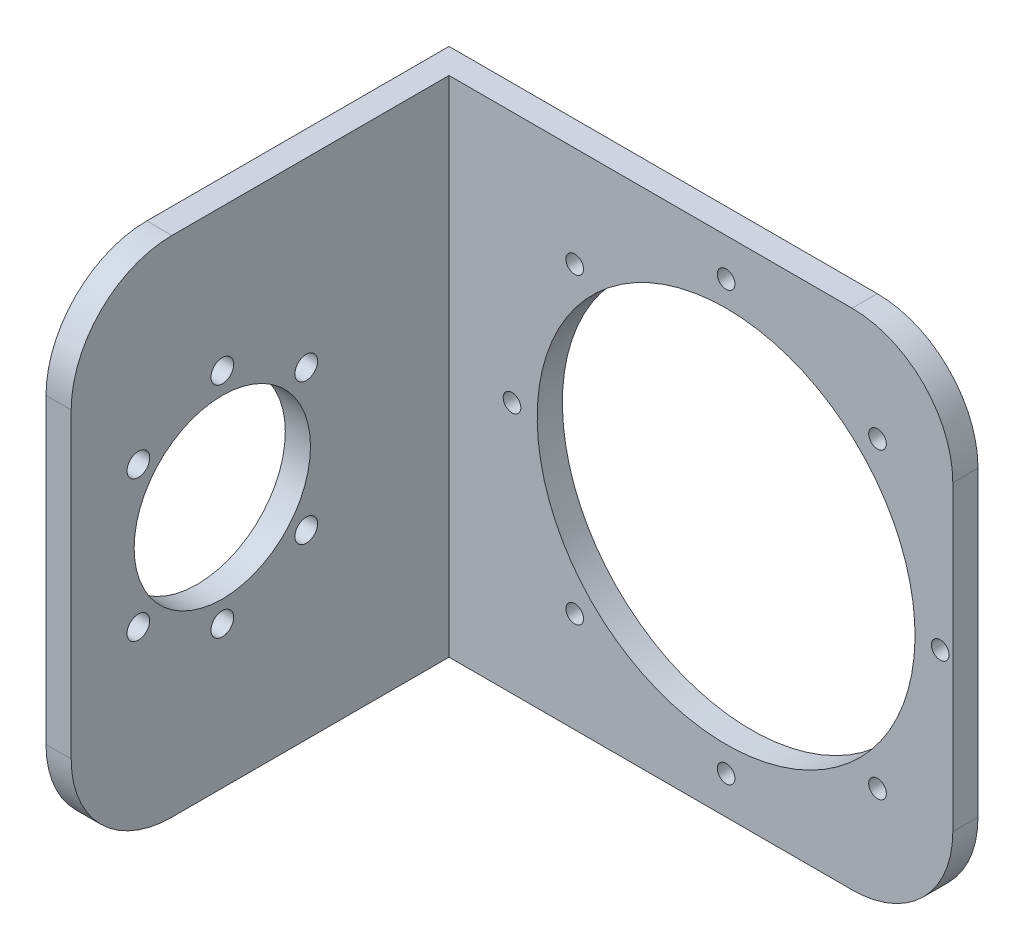
SolidWorks part; units mm, degrees
material "6061 合金"
ref_plane "前视基准面" through (0, 0, 0) normal (0, 0, 1) x (1, 0, 0)
ref_plane "上视基准面" through (0, 0, 0) normal (0, 1, 0) x (1, 0, 0)
ref_plane "右视基准面" through (0, 0, 0) normal (1, 0, 0) x (0, 0, -1)
other "Configuration Table"
sketch "草图1" plane through (0, 0, 0) normal (1, 0, 0) x (0, 0, -1)
  line L0 (-83.5786, 0) -> (71.0535, 0) construction
  line L1 (0, 49.275) -> (0, -51.1598) construction
  line L3 (-40, 50) -> (40, 50)
  line L4 (-40, 50) -> (-40, -50)
  line L5 (-40, -50) -> (40, -50)
  line L6 (40, 50) -> (40, -50)
  dimension "D1" = 80
  dimension "D2" = 100
extrude "凸台-拉伸1" add sketch "草图1" along normal blind 5
sketch "草图3" plane through (5, 0, 0) normal (1, 0, 0) x (0, 0, -1)
  line L0 (40, 50) -> (-40, 50) construction
  line L1 (35, 50) -> (40, 50)
  line L2 (35, 50) -> (35, -50)
  line L3 (35, -50) -> (40, -50)
  line L4 (40, 50) -> (40, -50)
  line L5 (0, 33.3664) -> (0, -30.3664) construction
  line L6 (-35, -50) -> (-40, -50)
  line L7 (-40, 50) -> (-40, -50)
  line L8 (-35, 50) -> (-40, 50)
  line L9 (-35, 50) -> (-35, -50)
  dimension "D1" = 5
extrude "凸台-拉伸2" add sketch "草图3" along normal blind 100 contours L2 L1 L4 L3
sketch "草图4" plane through (0, 0, 0) normal (-1, 0, 0) x (0, 0, 1)
  line L0 (-42.5996, 0) -> (43.5329, 0) construction
  line L1 (10, 63.7809) -> (10, -33.233) construction
  line L2 (40, 50) -> (40, -50) construction
  line L3 (10, 0) -> (26.6615, 13.9806) construction
  circle A0 centre (10, 0) radius 46 construction
  circle A1 centre (10, 0) radius 21.75 construction
  circle A2 centre (10, 21.75) radius 2.25
  circle A15 centre (26.6615, 13.9806) radius 2.25
  circle A16 centre (-6.6615, 13.9806) radius 2.25
  circle A17 centre (10, -21.75) radius 2.25
  circle A18 centre (26.6615, -13.9806) radius 2.25
  circle A19 centre (-6.6615, -13.9806) radius 2.25
  circle A20 centre (10, 0) radius 17.5
  point P24 (10, 0)
  point P28 (10, 0)
  dimension "D2" = 92
  dimension "D3" = 43.5
  dimension "D4" = 4.5
  dimension "D6" = 35
  dimension "D1" = 30
  dimension "D5" = 50
extrude "切除-拉伸1" cut sketch "草图4" against normal blind 100
sketch "草图5" plane through (0, 0, -40) normal (0, 0, -1) x (-1, 0, 0)
  line L0 (0, 0) -> (-122.5794, 0) construction
  line L1 (0, -50) -> (0, 50) construction
  circle A0 centre (-60, 0) radius 42.5 construction
  circle A1 centre (-60, 42.5) radius 1.75
  circle A2 centre (-29.948, 30.052) radius 1.75
  circle A3 centre (-17.5, 0) radius 1.75
  circle A4 centre (-29.948, -30.052) radius 1.75
  circle A5 centre (-60, -42.5) radius 1.75
  circle A6 centre (-90.052, -30.052) radius 1.75
  circle A7 centre (-102.5, 0) radius 1.75
  circle A8 centre (-90.052, 30.052) radius 1.75
  circle A9 centre (-60, 0) radius 37.5
  point P25 (-60, 0)
  dimension "D1" = 85
  dimension "D3" = 3.5
  dimension "D5" = 75
  dimension "D2" = 60
  dimension "D4" = 8
extrude "切除-拉伸2" cut sketch "草图5" against normal blind 22
fillet "圆角1" radius 20 4 edges at (105, -50, -37.5) (105, 50, -37.5) (2.5, 50, 40) (2.5, -50, 40)
